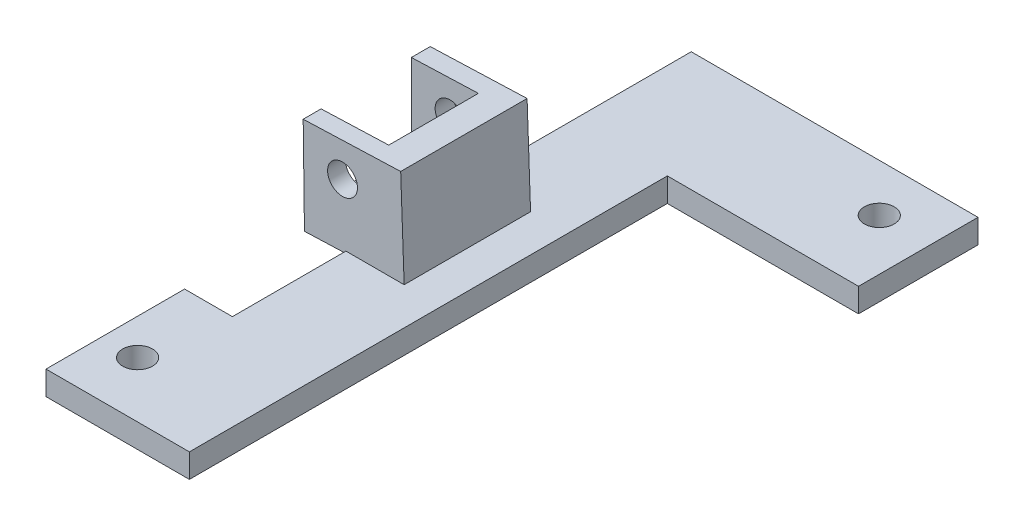
SolidWorks part; units mm, degrees
ref_plane "Front Plane" through (0, 0, 0) normal (0, 0, 1) x (1, 0, 0)
ref_plane "Top Plane" through (0, 0, 0) normal (0, 1, 0) x (1, 0, 0)
ref_plane "Right Plane" through (0, 0, 0) normal (1, 0, 0) x (0, 0, -1)
sketch "Sketch1" plane through (0, 0, 0) normal (0, 0, 1) x (1, 0, 0)
  line L0 (337.3168, 116.8505) -> (338.0523, 96.3659)
  line L1 (330.9022, 116.6201) -> (352.1622, 117.3835) construction
  line L2 (338.0523, 96.3659) -> (359.2436, 97.1267)
  line L3 (359.2436, 97.1267) -> (358.5081, 117.6113)
  line L4 (358.5081, 117.6113) -> (337.3168, 116.8505)
  line L5 (330.7578, 99.9164) -> (346.4865, 100.4811) construction
  line L6 (330.7578, 99.9164) -> (346.4865, 100.4811)
  line L7 (337.9156, 100.1734) -> (346.4865, 100.4811)
  arc A0 (346.4865, 100.4811) -> (352.6762, 103.0671) centre (346.1447, 110) ccw construction
  arc A1 (352.6762, 103.0671) -> (352.1622, 117.3835) centre (346.1447, 110) ccw construction
  arc A2 (346.4865, 100.4811) -> (352.6762, 103.0671) centre (346.1447, 110) ccw
  arc A3 (352.6762, 103.0671) -> (352.1622, 117.3835) centre (346.1447, 110) ccw
  arc A4 (352.1622, 117.3835) -> (352.6762, 103.0671) centre (346.1447, 110) cw
  arc A5 (352.6762, 103.0671) -> (346.4865, 100.4811) centre (346.1447, 110) cw
  dimension "D1" = 6.35
  dimension "D2" = 3.81
extrude "Boss-Extrude2" add sketch "Sketch1" against normal blind 23.0618 contours A3 A2 L6 L0 L2 L3 L4
sketch "Sketch5" plane through (0, 0, -23.0618) normal (0, 0, -1) x (-1, 0, 0)
  line L0 (-352.1622, 117.3835) -> (-337.9156, 116.872)
  line L1 (-337.9156, 116.872) -> (-337.9156, 100.1734)
  line L2 (-337.9156, 100.1734) -> (-346.4865, 100.4811)
  arc A0 (-346.4865, 100.4811) -> (-352.1622, 117.3835) centre (-346.1447, 110) cw
  circle A1 centre (-346.1447, 110) radius 3.175 construction
  circle A2 centre (-346.1447, 110) radius 3.175
  circle A3 centre (-346.1447, 110) radius 3.175
  arc M5 (-346.4865, 100.4811) -> (-352.1622, 117.3835) centre (-346.1447, 110) cw
  line M10 (-337.9156, 100.1734) -> (-346.4865, 100.4811)
extrude "Boss-Extrude3" add sketch "Sketch5" against normal up to surface (4.0118 mm away) contours L1 L0 A2 M5 M10
sketch "Sketch6" plane through (0, 0, 0) normal (0, 0, 1) x (1, 0, 0)
  line L0 (337.7808, 116.8671) -> (338.0523, 96.3659)
  line L1 (330.9022, 116.6201) -> (352.1622, 117.3835) construction
  line L2 (338.0523, 96.3659) -> (359.2436, 97.1267)
  line L3 (359.2436, 97.1267) -> (358.5081, 117.6113)
  line L4 (358.5081, 117.6113) -> (352.1622, 117.3835) construction
  line L5 (359.2436, 97.1267) -> (358.5081, 117.6113) construction
  line L6 (358.5081, 117.6113) -> (337.7808, 116.8671)
  circle A0 centre (346.1447, 110) radius 3.175
extrude "Boss-Extrude5" add sketch "Sketch6" along normal blind 3.81
ref_plane "Plane1" through (0, 97.1267, 0) normal (0, 1, 0) x (1, 0, 0)
sketch "Sketch7" plane through (0, 97.1267, 0) normal (0, 1, 0) x (1, 0, 0)
  line L0 (367.1845, -32.004) -> (367.1845, -57.404)
  line L2 (346.8645, 44.958) -> (346.8645, -27.94)
  line L4 (367.1845, 44.196) -> (367.1845, -32.004)
  line L5 (367.1845, -57.404) -> (336.7045, -57.404)
  line L6 (336.7045, -57.404) -> (336.7045, -27.94)
  line L7 (336.7045, -27.94) -> (346.8645, -27.94)
  line L8 (346.8645, 44.958) -> (346.8645, 69.596)
  line L9 (346.8645, 69.596) -> (407.8245, 69.596)
  line L10 (407.8245, 69.596) -> (407.8245, 44.196)
  line L11 (407.8245, 44.196) -> (367.1845, 44.196)
  circle A0 centre (396.9775, 59.4568) radius 3.175
  circle A1 centre (344.3245, -45.5528) radius 3.175
  circle A2 centre (344.3245, -45.5528) radius 3.175 construction
  dimension "D5" = 25.4
  dimension "D8" = 6.35
  dimension "D9" = 6.35
  dimension "D1" = 30.48
  dimension "D2" = 60.96
  dimension "D3" = 25.4
  dimension "D4" = 76.2
  dimension "D6" = 72.898
  dimension "D7" = 24.638
  dimension "D10" = 127
  dimension "D11" = 20.32
  dimension "D12" = 53.594
  dimension "D13" = 7.62
extrude "Boss-Extrude6" add sketch "Sketch7" against normal blind 5.08 contours L2 L7 L6 L5 L0 L4 L11 L10 L9 L8 | A0
